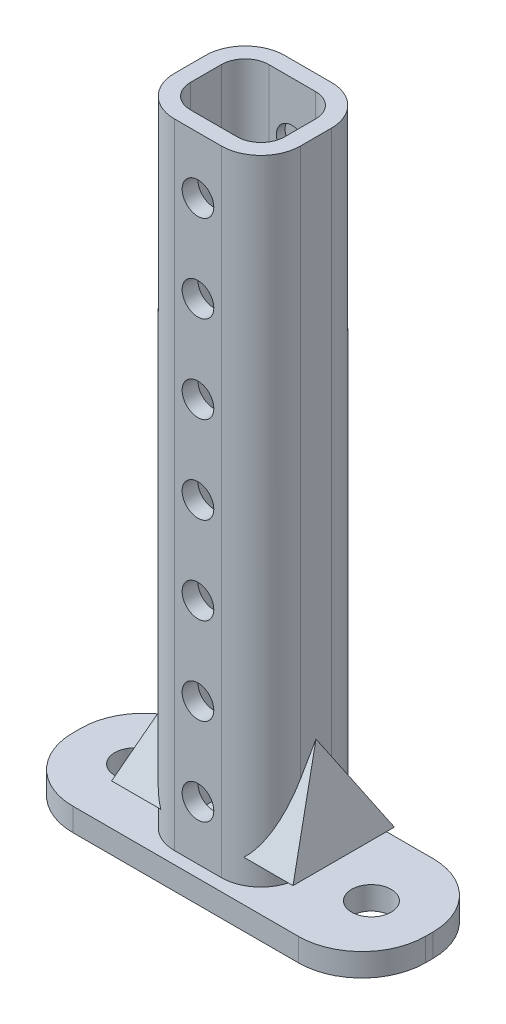
SolidWorks part; units mm, degrees
ref_plane "前视基准面" through (0, 0, 0) normal (0, 0, 1) x (1, 0, 0)
ref_plane "上视基准面" through (0, 0, 0) normal (0, 1, 0) x (1, 0, 0)
ref_plane "右视基准面" through (0, 0, 0) normal (1, 0, 0) x (0, 0, -1)
other "Configuration Table"
sketch "草图1" plane through (0, 0, 0) normal (0, 1, 0) x (1, 0, 0)
  line L1 (-14.25, 8.5) -> (14.25, 8.5)
  line L2 (-22.25, 0.5) -> (-22.25, -0.5)
  line L3 (-14.25, -8.5) -> (14.25, -8.5)
  line L4 (22.25, 0.5) -> (22.25, -0.5)
  line L5 (-22.25, 8.5) -> (22.25, -8.5) construction
  line L6 (-22.25, -8.5) -> (22.25, 8.5) construction
  arc A0 (14.25, -8.5) -> (22.25, -0.5) centre (14.25, -0.5) ccw
  arc A1 (22.25, 0.5) -> (14.25, 8.5) centre (14.25, 0.5) ccw
  arc A2 (-14.25, -8.5) -> (-22.25, -0.5) centre (-14.25, -0.5) cw
  arc A3 (-14.25, 8.5) -> (-22.25, 0.5) centre (-14.25, 0.5) ccw
  point P0 (0, 0)
  dimension "D3" = 8
  dimension "D1" = 44.5
  dimension "D2" = 17
extrude "凸台-拉伸1" add sketch "草图1" along normal blind 2.9
sketch "草图3" plane through (0, 2.9, 0) normal (0, 1, 0) x (1, 0, 0)
  line L0 (14.25, 8.5) -> (-14.25, 8.5) construction
  line L1 (-2.95, 6.95) -> (2.95, 6.95)
  line L2 (-7.95, 1.95) -> (-7.95, -1.95)
  line L3 (-2.95, -6.95) -> (2.95, -6.95)
  line L4 (7.95, 1.95) -> (7.95, -1.95)
  line L5 (-7.95, 6.95) -> (7.95, -6.95) construction
  line L6 (-7.95, -6.95) -> (7.95, 6.95) construction
  arc A0 (-7.95, -1.95) -> (-2.95, -6.95) centre (-2.95, -1.95) ccw
  arc A1 (2.95, -6.95) -> (7.95, -1.95) centre (2.95, -1.95) ccw
  arc A2 (2.95, 6.95) -> (7.95, 1.95) centre (2.95, 1.95) cw
  arc A3 (-2.95, 6.95) -> (-7.95, 1.95) centre (-2.95, 1.95) ccw
  point P0 (0, 0)
  dimension "D1" = 5
  dimension "D2" = 1.55
  dimension "D3" = 15.9
extrude "凸台-拉伸2" add sketch "草图3" along normal blind 80
sketch "草图4" plane through (0, 82.9, 0) normal (0, 1, 0) x (1, 0, 0)
  line L13 (5.95, -1.95) -> (5.95, 1.95)
  line L14 (2.95, 4.95) -> (-2.95, 4.95)
  line L15 (-5.95, 1.95) -> (-5.95, -1.95)
  line L16 (5.95, -1.95) -> (5.95, 1.95)
  line L17 (2.95, 4.95) -> (-2.95, 4.95)
  line L18 (-5.95, 1.95) -> (-5.95, -1.95)
  line L20 (-2.95, -4.95) -> (2.95, -4.95)
  line L21 (-2.95, -4.95) -> (2.95, -4.95)
  arc A9 (5.95, 1.95) -> (2.95, 4.95) centre (2.95, 1.95) ccw
  arc A10 (-2.95, 4.95) -> (-5.95, 1.95) centre (-2.95, 1.95) ccw
  arc A11 (5.95, 1.95) -> (2.95, 4.95) centre (2.95, 1.95) ccw
  arc A12 (-2.95, 4.95) -> (-5.95, 1.95) centre (-2.95, 1.95) ccw
  arc A16 (2.95, -4.95) -> (5.95, -1.95) centre (2.95, -1.95) ccw
  arc A17 (-5.95, -1.95) -> (-2.95, -4.95) centre (-2.95, -1.95) ccw
  arc A18 (2.95, -4.95) -> (5.95, -1.95) centre (2.95, -1.95) ccw
  arc A19 (-5.95, -1.95) -> (-2.95, -4.95) centre (-2.95, -1.95) ccw
  dimension "D1" = 2
  dimension "D2" = 2
extrude "切除-拉伸1" cut sketch "草图4" against normal blind 80
sketch "草图5" plane through (0, 2.9, 0) normal (0, 1, 0) x (1, 0, 0)
  line L0 (0, 0) -> (-16.269, 0) construction
  line L1 (0, 0) -> (0, 9.6241) construction
  line L2 (-7.95, 1.95) -> (-7.95, -1.95) construction
  circle A0 centre (-14.95, 0) radius 2.5
  circle A1 centre (14.95, 0) radius 2.5
  dimension "D1" = 5
  dimension "D2" = 7
extrude "切除-拉伸2" cut sketch "草图5" against normal blind 80
sketch "草图7" plane through (0, 0, 0) normal (0, -1, 0) x (-1, 0, 0)
  line L1 (2.95, -6.95) -> (-2.95, -6.95)
  line L2 (7.95, -1.95) -> (7.95, 1.95)
  line L3 (2.95, 6.95) -> (-2.95, 6.95)
  line L4 (-7.95, -1.95) -> (-7.95, 1.95)
  line L5 (7.95, -6.95) -> (-7.95, 6.95) construction
  line L6 (7.95, 6.95) -> (-7.95, -6.95) construction
  arc A0 (7.95, 1.95) -> (2.95, 6.95) centre (2.95, 1.95) ccw
  arc A1 (-2.95, 6.95) -> (-7.95, 1.95) centre (-2.95, 1.95) ccw
  arc A2 (-2.95, -6.95) -> (-7.95, -1.95) centre (-2.95, -1.95) cw
  arc A3 (2.95, -6.95) -> (7.95, -1.95) centre (2.95, -1.95) ccw
  point P0 (0, 0)
  point P18 (7.95, 0)
  dimension "D1" = 5
  dimension "D2" = 15.9
  dimension "D3" = 13.9
extrude "凸台-拉伸3" add sketch "草图7" along normal blind 1.5
sketch "草图8" plane through (0, 0, 6.95) normal (0, 0, 1) x (1, 0, 0)
  line L0 (0, 82.9) -> (0, 31.2727) construction
  line L1 (-2.95, 82.9) -> (2.95, 82.9) construction
  circle A0 centre (0, 75.7208) radius 2
  circle A1 centre (0, 64.7208) radius 2
  circle A2 centre (0, 53.7208) radius 2
  circle A3 centre (0, 42.7208) radius 2
  circle A4 centre (0, 31.7208) radius 2
  circle A5 centre (0, 20.7208) radius 2
  circle A6 centre (0, 9.7208) radius 2
  dimension "D1" = 7
extrude "切除-拉伸3" cut sketch "草图8" against normal blind 13
sketch "草图9" plane through (-7.95, 0, 0) normal (-1, 0, 0) x (0, 0, 1)
  line L0 (0, 2.9) -> (0, 32.2047) construction
  line L1 (-1.95, 2.9) -> (1.95, 2.9) construction
  line L3 (0, 17.0815) -> (-6.3979, 6)
  line L4 (-6.3979, 6) -> (6.3979, 6)
  line L5 (6.3979, 6) -> (0, 17.0815)
  circle A0 centre (0, 9.6938) radius 3.6938 construction
  dimension "D1" = 3.1
extrude "凸台-拉伸4" add sketch "草图9" along normal mid plane 7
sketch "草图10" plane through (0, 0, 6.95) normal (0, 0, 1) x (1, 0, 0)
  line L0 (-11.45, 6) -> (-7.95, 17.0815)
  line L1 (-7.95, 17.0815) -> (-15.5568, 23.6018)
  line L2 (-15.5568, 23.6018) -> (-11.45, 6)
extrude "切除-拉伸4" cut sketch "草图10" against normal blind 50
ref_plane "基准面8" through (-2.95, 82.9, -4.95) normal (-1, 0, 0) x (0, 0, 1)
sketch "草图12" plane through (0, 82.9, 0) normal (0, 1, 0) x (1, 0, 0)
  line L8 (-2.95, -4.95) -> (2.95, -4.95)
  line L9 (5.95, -1.95) -> (5.95, 1.95)
  line L10 (2.95, 4.95) -> (-2.95, 4.95)
  line L11 (-5.95, 1.95) -> (-5.95, -1.95)
  line L12 (-2.95, -4.95) -> (2.95, -4.95)
  line L13 (5.95, -1.95) -> (5.95, 1.95)
  line L14 (2.95, 4.95) -> (-2.95, 4.95)
  line L15 (-5.95, 1.95) -> (-5.95, -1.95)
  arc A8 (-5.95, -1.95) -> (-2.95, -4.95) centre (-2.95, -1.95) ccw
  arc A9 (2.95, -4.95) -> (5.95, -1.95) centre (2.95, -1.95) ccw
  arc A10 (5.95, 1.95) -> (2.95, 4.95) centre (2.95, 1.95) ccw
  arc A11 (-2.95, 4.95) -> (-5.95, 1.95) centre (-2.95, 1.95) ccw
  arc A12 (-5.95, -1.95) -> (-2.95, -4.95) centre (-2.95, -1.95) ccw
  arc A13 (2.95, -4.95) -> (5.95, -1.95) centre (2.95, -1.95) ccw
  arc A14 (5.95, 1.95) -> (2.95, 4.95) centre (2.95, 1.95) ccw
  arc A15 (-2.95, 4.95) -> (-5.95, 1.95) centre (-2.95, 1.95) ccw
  dimension "D1" = 2
extrude "切除-拉伸5" cut sketch "草图12" against normal blind 80
mirror "镜向2" about plane through (0, 0, 0) normal (1, 0, 0) of "凸台-拉伸4"
mirror "镜向3" about plane through (0, 0, 0) normal (1, 0, 0) of "切除-拉伸4", "切除-拉伸5"
